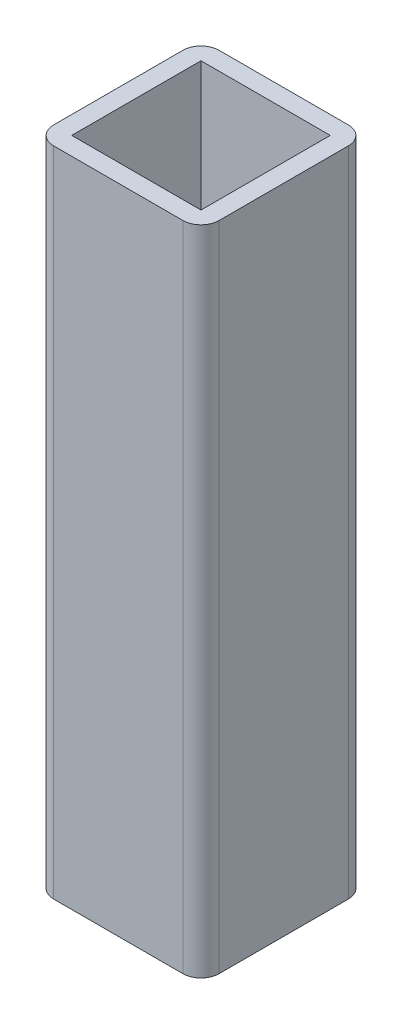
SolidWorks part; units mm, degrees
material "Plain Carbon Steel"
ref_plane "Front Plane" through (0, 0, 0) normal (0, 0, 1) x (1, 0, 0)
ref_plane "Top Plane" through (0, 0, 0) normal (0, 1, 0) x (1, 0, 0)
ref_plane "Right Plane" through (0, 0, 0) normal (1, 0, 0) x (0, 0, -1)
sketch "Sketch1" plane through (0, 0, 0) normal (0, 1, 0) x (1, 0, 0)
  line L1 (2.8, 0) -> (22.8, 0)
  line L2 (0, -2.8) -> (0, -22.8)
  line L3 (2.8, -25.6) -> (22.8, -25.6)
  line L4 (25.6, -2.8) -> (25.6, -22.8)
  arc A0 (22.8, 0) -> (25.6, -2.8) centre (22.8, -2.8) cw
  arc A1 (22.8, -25.6) -> (25.6, -22.8) centre (22.8, -22.8) ccw
  arc A2 (0, -22.8) -> (2.8, -25.6) centre (2.8, -22.8) ccw
  arc A3 (2.8, 0) -> (0, -2.8) centre (2.8, -2.8) ccw
  point P7 (25.6, 0)
  point P10 (25.6, -25.6)
  point P15 (0, 0)
  dimension "D2" = 2.8
  dimension "D1" = 25.6
extrude "Boss-Extrude1" add sketch "Sketch1" along normal blind 100.91
sketch "Sketch3" plane through (0, 0, 0) normal (0, -1, 0) x (-1, 0, 0)
  line L4 (-2.8, -2.8) -> (-22.8, -2.8)
  line L5 (-2.8, -2.8) -> (-2.8, -22.8)
  line L6 (-2.8, -22.8) -> (-22.8, -22.8)
  line L7 (-22.8, -2.8) -> (-22.8, -22.8)
  line L8 (-2.8, -2.8) -> (-22.8, -22.8) construction
  line L9 (-2.8, -22.8) -> (-22.8, -2.8) construction
  point P6 (-12.8, -12.8)
extrude "Cut-Extrude1" cut sketch "Sketch3" against normal blind 1040.5
